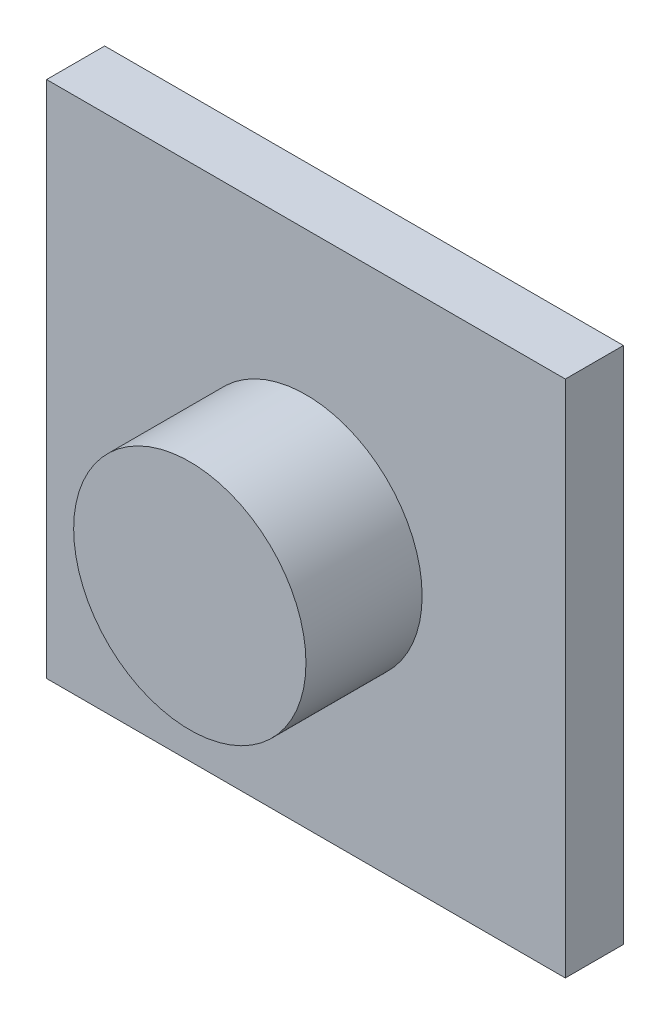
SolidWorks part; units mm, degrees
ref_plane "Front Plane" through (0, 0, 0) normal (0, 0, 1) x (1, 0, 0)
ref_plane "Top Plane" through (0, 0, 0) normal (0, 1, 0) x (1, 0, 0)
ref_plane "Right Plane" through (0, 0, 0) normal (1, 0, 0) x (0, 0, -1)
sketch "Sketch1" plane through (0, 0, 0) normal (0, 0, 1) x (1, 0, 0)
  circle A0 centre (0, 0) radius 100
  dimension "D1" = 200
extrude "Boss-Extrude1" add sketch "Sketch1" along normal blind 100
sketch "Sketch2" plane through (0, 0, 0) normal (0, 0, -1) x (-1, 0, 0)
  line L1 (-223.3, 223.3) -> (223.3, 223.3)
  line L2 (-223.3, 223.3) -> (-223.3, -223.3)
  line L3 (-223.3, -223.3) -> (223.3, -223.3)
  line L4 (223.3, 223.3) -> (223.3, -223.3)
  line L5 (-223.3, 223.3) -> (223.3, -223.3) construction
  line L6 (-223.3, -223.3) -> (223.3, 223.3) construction
  point P0 (0, 0)
  dimension "D1" = 446.6
  dimension "D2" = 446.6
extrude "Boss-Extrude2" add sketch "Sketch2" along normal blind 50
